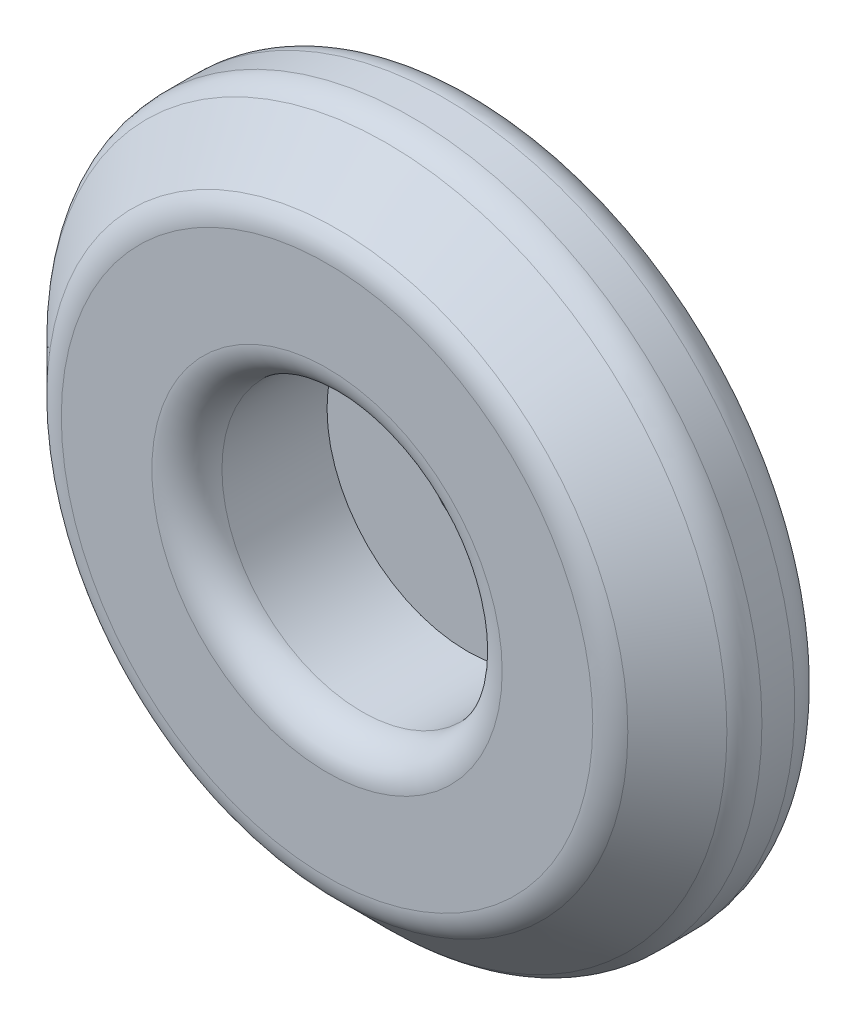
SolidWorks part; units mm, degrees
ref_plane "Front Plane" through (0, 0, 0) normal (0, 0, 1) x (1, 0, 0)
ref_plane "Top Plane" through (0, 0, 0) normal (0, 1, 0) x (1, 0, 0)
ref_plane "Right Plane" through (0, 0, 0) normal (1, 0, 0) x (0, 0, -1)
sketch "Sketch1" plane through (0, 0, 0) normal (0, 0, 1) x (1, 0, 0)
  circle A0 centre (0, 0) radius 63.5
  dimension "D1" = 127
extrude "Boss-Extrude1" add sketch "Sketch1" along normal blind 50.8
sketch "Sketch2" plane through (0, 0, 50.8) normal (0, 0, 1) x (1, 0, 0)
  circle A0 centre (0, 0) radius 25.4
  dimension "D1" = 50.8
extrude "Cut-Extrude2" cut sketch "Sketch2" against normal blind 25.4
sketch "Sketch3" plane through (0, 0, 25.4) normal (0, 0, 1) x (1, 0, 0)
  circle A0 centre (0, 0) radius 6.35
  dimension "D1" = 12.7
extrude "Cut-Extrude3" cut sketch "Sketch3" against normal through all
sketch "Sketch4" plane through (0, 0, 0) normal (1, 0, 0) x (0, 0, -1)
  line L0 (0, 63.5) -> (-25.4, 63.5)
  line L1 (0, -63.5) -> (0, 63.5) construction
  line L2 (-25.4, 63.5) -> (0, 6.35)
  line L3 (0, 6.35) -> (0, 63.5)
  line L4 (0, 0) -> (26.5228, 0) construction
  dimension "D1" = 25.4
  dimension "D2" = 6.35
revolve "Cut-Revolve1" cut sketch "Sketch4" angle 360 about L4
ref_plane "Plane1" through (0, 0, 0) normal (0, 0, 1) x (1, 0, 0)
sketch "Sketch6" plane through (0, 0, 0) normal (0, 0, 1) x (1, 0, 0)
  circle A0 centre (0, 0) radius 12.7
  dimension "D1" = 25.4
extrude "Cut-Extrude4" cut sketch "Sketch6" along normal blind 6.35
chamfer "Chamfer1" distance 12.7 angle 45 1 edges at (63.5, 0, 50.8)
fillet "Fillet1" radius 6.35 4 edges at (25.4, 0, 50.8) (50.8, 0, 50.8) (63.5, 0, 38.1) (63.5, 0, 25.4)
